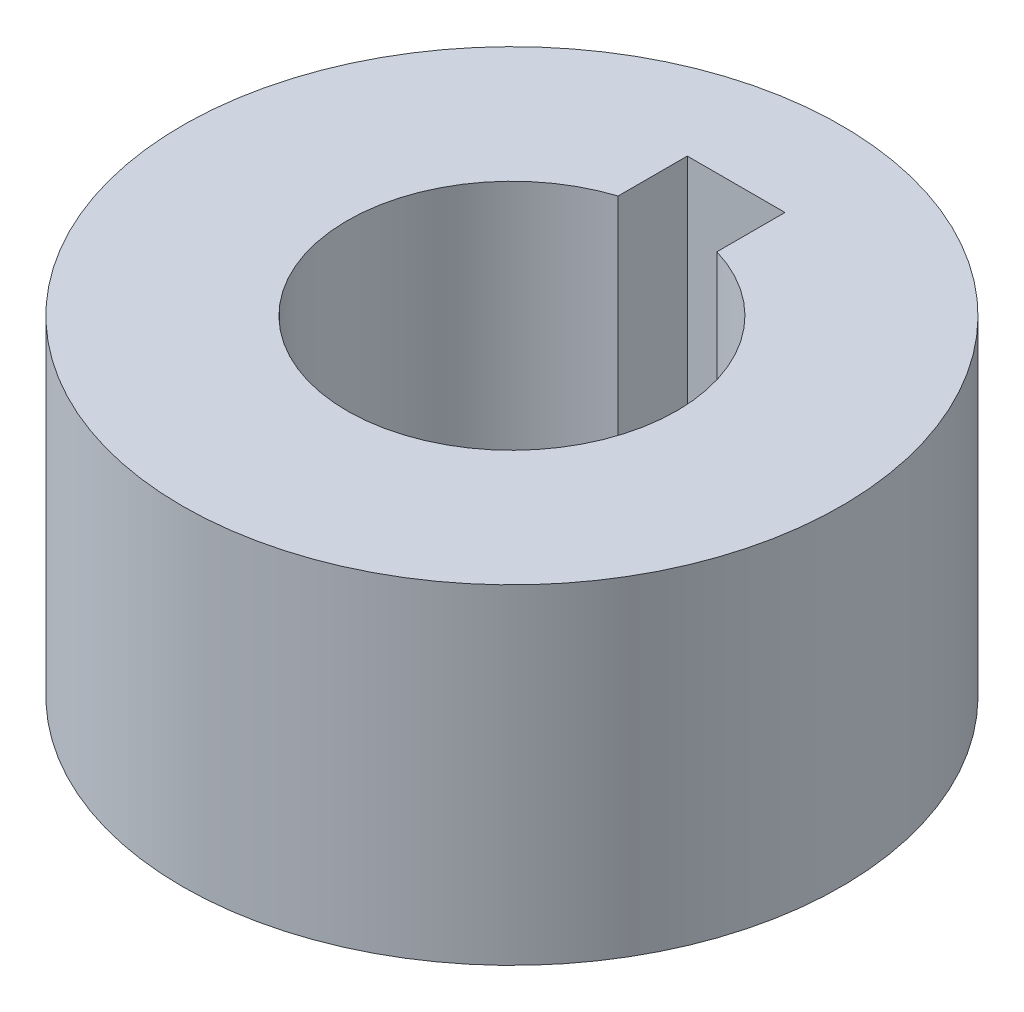
SolidWorks part; units mm, degrees
ref_plane "정면" through (0, 0, 0) normal (0, 0, 1) x (1, 0, 0)
ref_plane "윗면" through (0, 0, 0) normal (0, 1, 0) x (1, 0, 0)
ref_plane "우측면" through (0, 0, 0) normal (1, 0, 0) x (0, 0, -1)
sketch "스케치1" plane through (0, 0, 0) normal (0, 1, 0) x (1, 0, 0)
  line L0 (-1.5361, 4.7582) -> (-1.5361, 6.8568)
  line L1 (-1.5361, 6.8568) -> (1.4282, 6.8568)
  line L2 (1.4282, 6.8568) -> (1.4282, 4.7917)
  circle A0 centre (0, 0) radius 10
  circle A1 centre (0, 0) radius 5
  circle A2 centre (0, 0) radius 5
  dimension "D1" = 20
  dimension "D2" = 10
extrude "보스-돌출1" add sketch "스케치1" along normal blind 10 contours A0 A1
